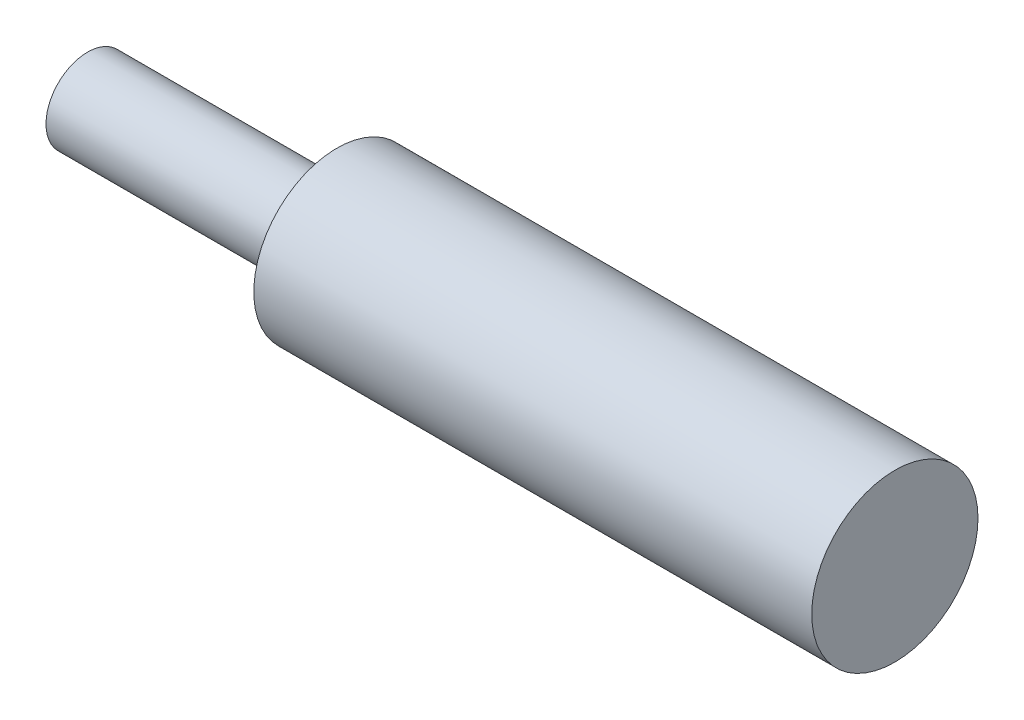
SolidWorks part; units mm, degrees
ref_plane "Front" through (0, 0, 0) normal (0, 0, 1) x (1, 0, 0)
ref_plane "Top" through (0, 0, 0) normal (0, 1, 0) x (1, 0, 0)
ref_plane "Right" through (0, 0, 0) normal (1, 0, 0) x (0, 0, -1)
sketch "Sketch3" plane through (2753.7937, 0, 0) normal (-1, 0, 0) x (0, 0, 1)
  circle A0 centre (23.734, 11.5) radius 4 construction
  circle A1 centre (23.734, 11.5) radius 4
extrude "Base-Extrude" add sketch "Sketch3" against normal up to surface (77.7 mm away)
sketch "Sketch4" plane through (2831.4937, 0, 0) normal (-1, 0, 0) x (0, 0, 1)
  circle A1 centre (23.734, 11.5) radius 8 construction
  circle A2 centre (23.734, 11.5) radius 8
extrude "Boss-Extrude1" add sketch "Sketch4" along normal up to surface (53.7 mm away)
